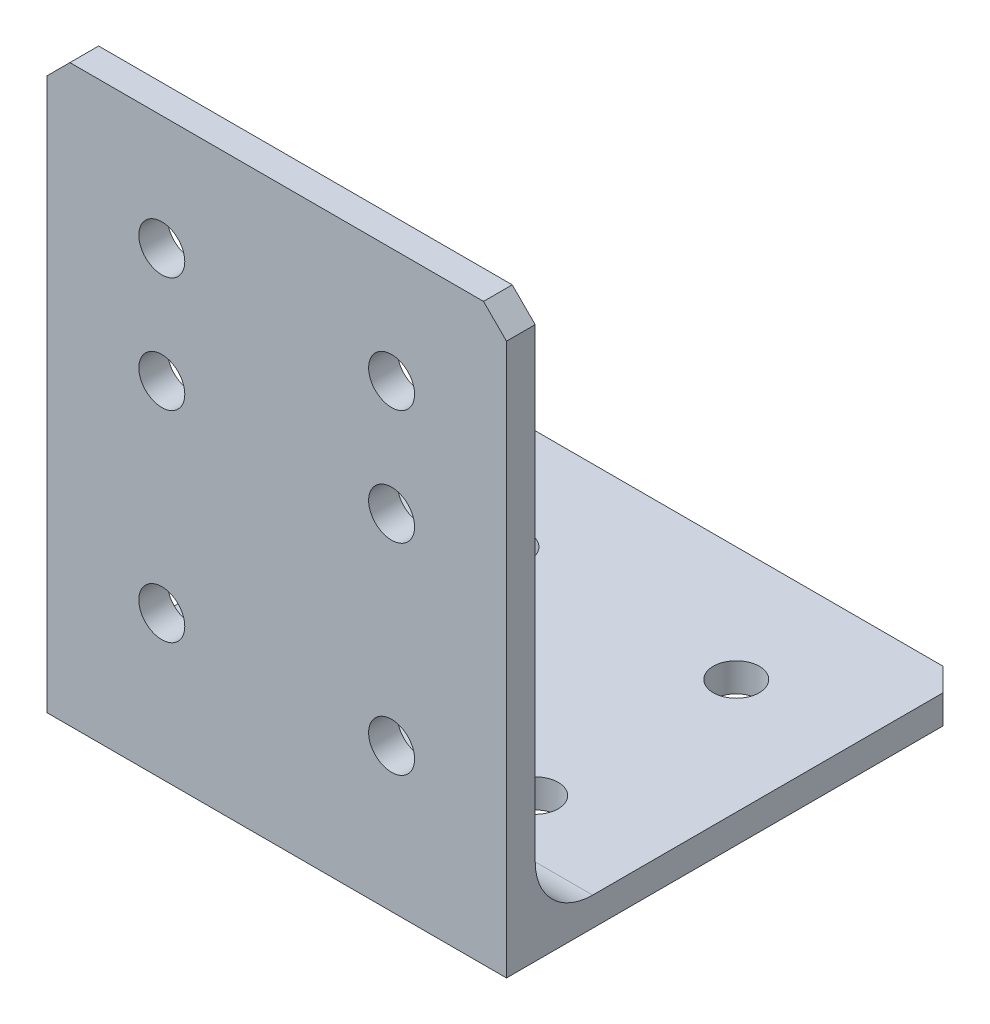
SolidWorks part; units mm, degrees
ref_plane "Front Plane" through (0, 0, 0) normal (0, 0, 1) x (1, 0, 0)
ref_plane "Top Plane" through (0, 0, 0) normal (0, 1, 0) x (1, 0, 0)
ref_plane "Right Plane" through (0, 0, 0) normal (1, 0, 0) x (0, 0, -1)
sketch "Sketch1" plane through (0, 0, 0) normal (1, 0, 0) x (0, 0, -1)
  line L0 (0, 0) -> (0, 63.5)
  line L1 (0, 63.5) -> (3.175, 63.5)
  line L2 (3.175, 63.5) -> (3.175, 3.175)
  line L3 (3.175, 3.175) -> (50.8, 3.175)
  line L4 (50.8, 3.175) -> (50.8, 0)
  line L5 (50.8, 0) -> (0, 0)
  dimension "D1" = 63.5
  dimension "D2" = 3.175
  dimension "D3" = 50.8
extrude "Boss-Extrude1" add sketch "Sketch1" along normal blind 50.8
sketch "Sketch2" plane through (0, 0, 0) normal (0, 0, 1) x (1, 0, 0)
  line L2 (50.8, 0) -> (0, 0) construction
  line L4 (25.4, 0) -> (25.4, 63.5) construction
  line L5 (50.8, 63.5) -> (0, 63.5) construction
  circle A0 centre (12.7, 38.1) radius 2.54
  circle A1 centre (12.7, 15.875) radius 2.54
  circle A6 centre (12.7, 50.8) radius 2.54
  circle A7 centre (38.1, 50.8) radius 2.54
  circle A8 centre (38.1, 15.875) radius 2.54
  circle A9 centre (38.1, 38.1) radius 2.54
  dimension "D1" = 5.08
  dimension "D2" = 12.7
  dimension "D3" = 12.7
  dimension "D4" = 15.875
  dimension "D5" = 22.225
extrude "Cut-Extrude1" cut sketch "Sketch2" against normal through all
sketch "Sketch3" plane through (0, 0, 0) normal (0, -1, 0) x (1, 0, 0)
  line L0 (50.8, -50.8) -> (0, -50.8) construction
  line L1 (50.8, 0) -> (0, 0) construction
  line L2 (50.8, 0) -> (50.8, -50.8) construction
  line L3 (0, 0) -> (0, -50.8) construction
  circle A0 centre (38.1, -38.1) radius 2.54
  circle A1 centre (38.1, -15.875) radius 2.54
  circle A2 centre (12.7, -38.1) radius 2.54
  circle A3 centre (12.7, -15.875) radius 2.54
  dimension "D1" = 5.08
  dimension "D2" = 12.7
  dimension "D3" = 15.875
  dimension "D4" = 12.7
  dimension "D5" = 12.7
  dimension "D6" = 22.225
extrude "Cut-Extrude2" cut sketch "Sketch3" against normal through all
fillet "Fillet1" radius 6.35 1 edges at (25.4, 3.175, -3.175)
chamfer "Chamfer1" distance 2.54 angle 45 4 edges at (50.8, 63.5, -1.5875) (0, 63.5, -1.5875) (50.8, 1.5875, -50.8) (0, 1.5875, -50.8)
